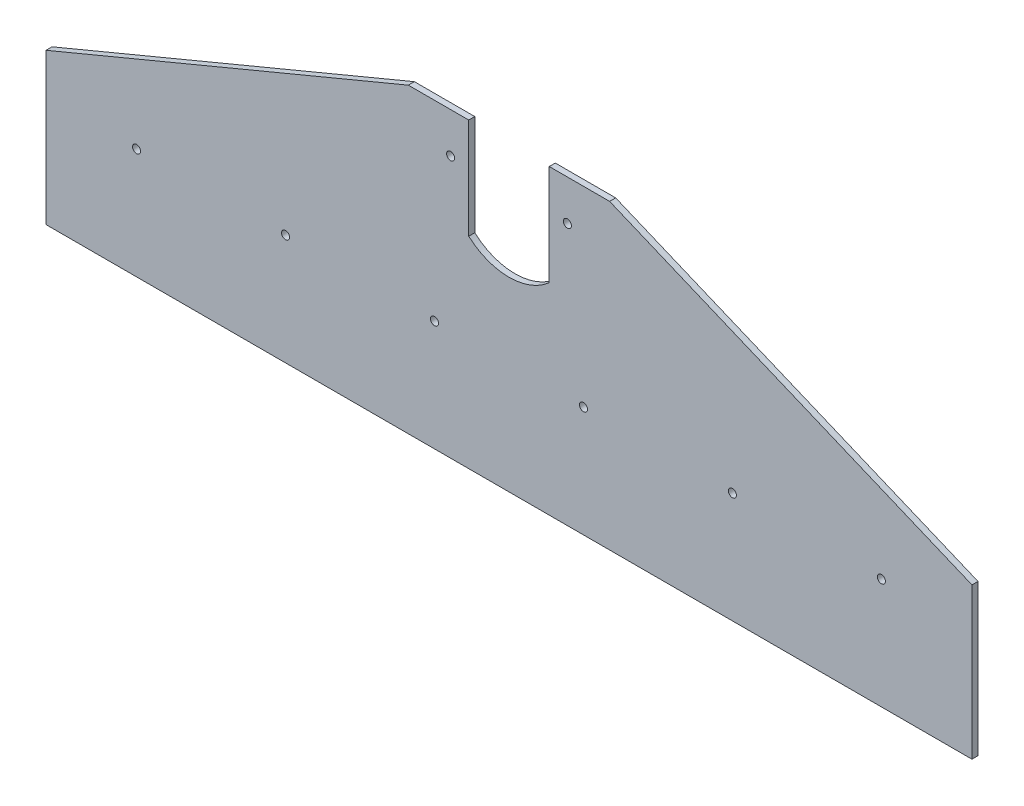
SolidWorks part; units mm, degrees
ref_plane "Ön Düzlem" through (0, 0, 0) normal (0, 0, 1) x (1, 0, 0)
ref_plane "Üst Düzlem" through (0, 0, 0) normal (0, 1, 0) x (1, 0, 0)
ref_plane "Sağ Düzlem" through (0, 0, 0) normal (1, 0, 0) x (0, 0, -1)
sketch "Çizim1" plane through (0, 0, 0) normal (0, 0, 1) x (1, 0, 0)
  line L0 (230, 0) -> (230, 150) construction
  line L1 (0, 0) -> (460, 0)
  line L2 (0, 0) -> (0, 75)
  line L4 (460, 0) -> (460, 75)
  line L5 (0, 75) -> (180, 150)
  line L6 (180, 150) -> (280, 150)
  line L7 (280, 150) -> (460, 75)
  dimension "D1" = 75
  dimension "D2" = 460
  dimension "D3" = 75
  dimension "D4" = 100
extrude "Yükseklik-Ekstrüzyon1" add sketch "Çizim1" along normal blind 3
sketch "Çizim2" plane through (0, 0, 3) normal (0, 0, 1) x (1, 0, 0)
  line L0 (0, 55) -> (460, 55) construction
  line L1 (0, 75) -> (0, 0) construction
  line L2 (460, 0) -> (460, 75) construction
  line L3 (0, 0) -> (460, 0) construction
  line L4 (230, 150) -> (230, 0) construction
  line L5 (280, 150) -> (180, 150) construction
  line L6 (191.5021, 130) -> (265.1639, 130) construction
  line L7 (210, 150) -> (250, 150)
  line L8 (210, 150) -> (210, 100)
  line L10 (250, 150) -> (250, 100)
  circle A0 centre (45, 55) radius 2
  circle A1 centre (119, 55) radius 2
  circle A2 centre (193, 55) radius 2
  circle A3 centre (267, 55) radius 2
  circle A4 centre (341, 55) radius 2
  circle A5 centre (415, 55) radius 2
  arc A6 (210, 100) -> (250, 100) centre (230, 122.3607) ccw
  circle A7 centre (201, 130) radius 2
  circle A8 centre (259, 130) radius 2
  point P35 (0, 0)
  dimension "D2" = 4
  dimension "D5" = 74
  dimension "D8" = 30
  dimension "D11" = 4
  dimension "D1" = 55
  dimension "D3" = 45
  dimension "D6" = 40
  dimension "D7" = 50
  dimension "D9" = 20
  dimension "D10" = 58
  dimension "D4" = 6
extrude "Kes-Ekstrüzyon1" cut sketch "Çizim2" against normal blind 3
